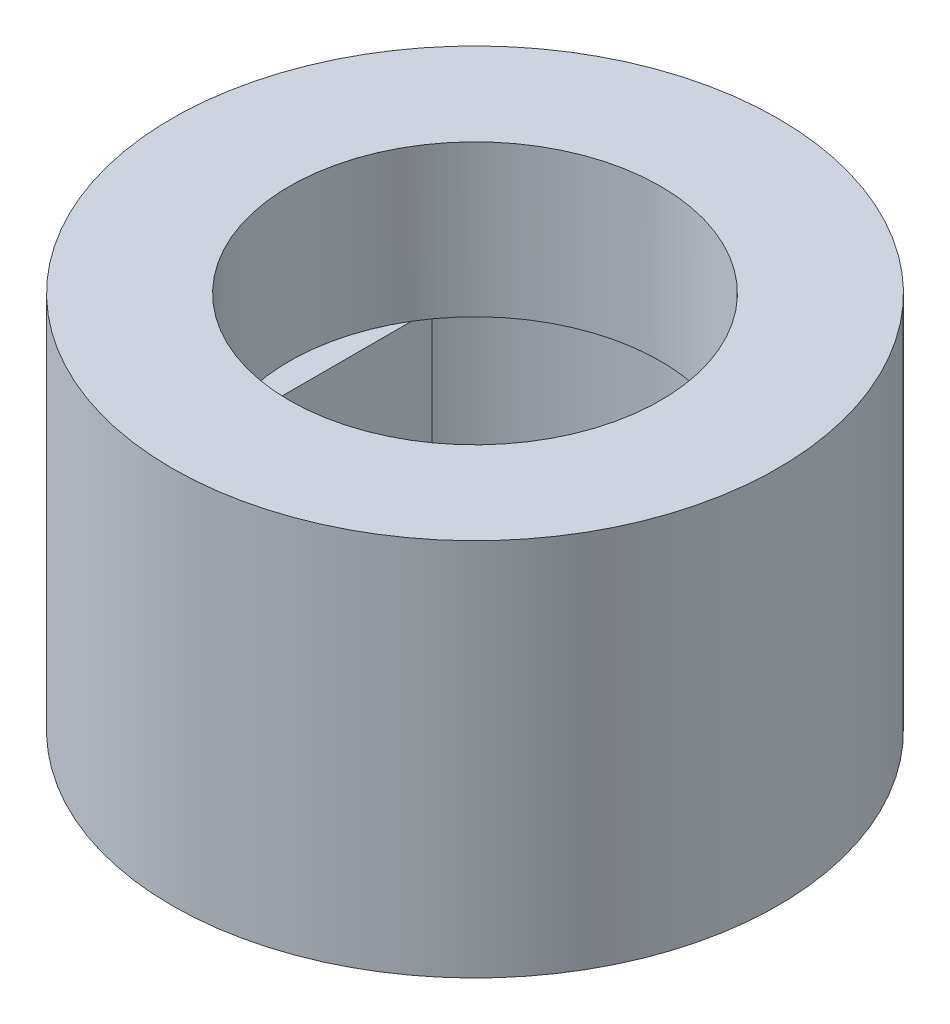
SolidWorks part; units mm, degrees
ref_plane "Front Plane" through (0, 0, 0) normal (0, 0, 1) x (1, 0, 0)
ref_plane "Top Plane" through (0, 0, 0) normal (0, 1, 0) x (1, 0, 0)
ref_plane "Right Plane" through (0, 0, 0) normal (1, 0, 0) x (0, 0, -1)
sketch "Sketch1" plane through (0, 0, 0) normal (0, 1, 0) x (1, 0, 0)
  circle A0 centre (0, 0) radius 5.08
  dimension "D1" = 10.16
extrude "Boss-Extrude1" add sketch "Sketch1" along normal blind 6.35
sketch "Sketch2" plane through (0, 0, 0) normal (0, 1, 0) x (1, 0, 0)
  line L0 (-2.667, -1.9469) -> (-2.667, 1.9469)
  line L1 (0, 0) -> (-2.667, 0) construction
  circle A0 centre (0, 0) radius 3.302
  dimension "D1" = 6.604
  dimension "D2" = 2.667
extrude "Cut-Extrude1" cut sketch "Sketch2" along normal blind 3.81
sketch "Sketch3" plane through (0, 6.35, 0) normal (0, 1, 0) x (1, 0, 0)
  circle A0 centre (0, 0) radius 3.1115
  dimension "D1" = 6.223
extrude "Cut-Extrude2" cut sketch "Sketch3" against normal blind 2.54
